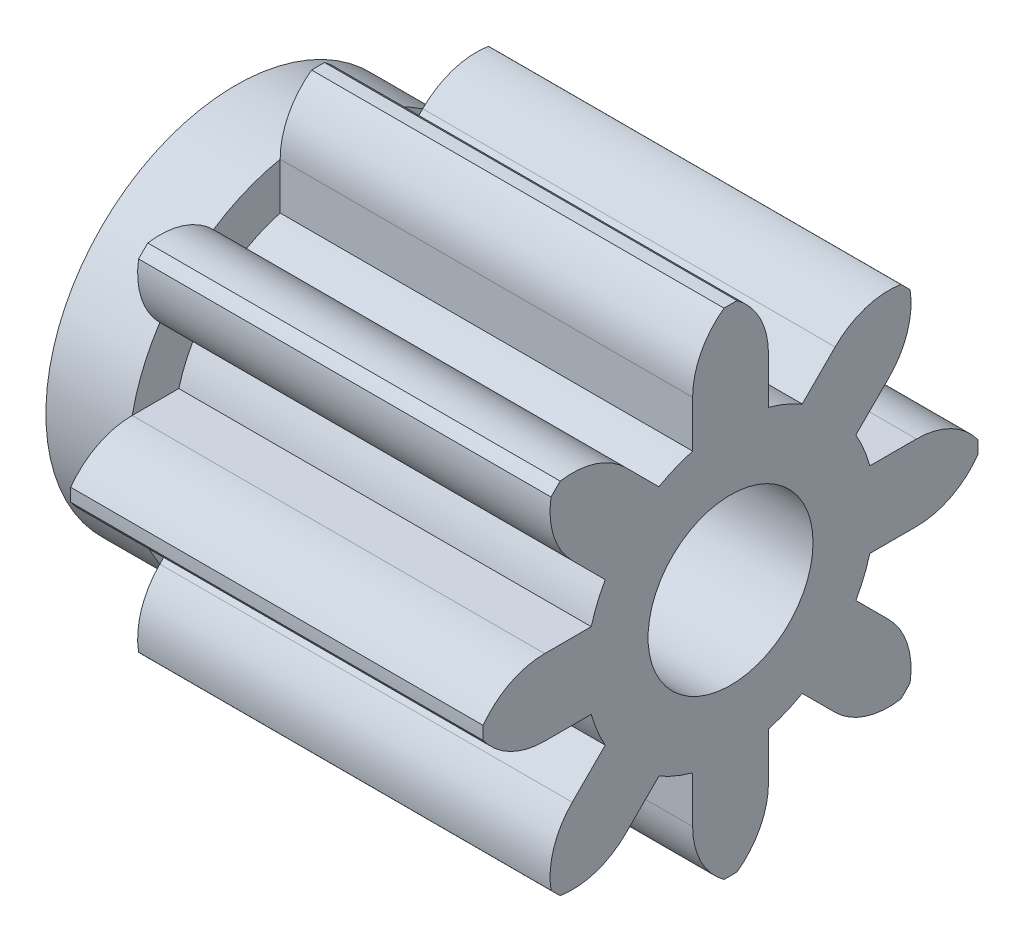
SolidWorks part; units mm, degrees
ref_plane "Front Plane" through (0, 0, 0) normal (0, 0, 1) x (1, 0, 0)
ref_plane "Top Plane" through (0, 0, 0) normal (0, 1, 0) x (1, 0, 0)
ref_plane "Right Plane" through (0, 0, 0) normal (1, 0, 0) x (0, 0, -1)
sketch "Sketch1" plane through (0, 0, 0) normal (1, 0, 0) x (0, 0, -1)
  circle A0 centre (0, 0) radius 2.3
  dimension "D1" = 4.6
extrude "Boss-Extrude1" add sketch "Sketch1" along normal blind 1
sketch "Sketch2" plane through (1, 0, 0) normal (1, 0, 0) x (0, 0, -1)
  circle A0 centre (0, 0) radius 1.75
  circle A1 centre (0, 0) radius 1
  dimension "D1" = 3.5
  dimension "D2" = 2
extrude "Boss-Extrude2" add sketch "Sketch2" along normal blind 5
sketch "Sketch3" plane through (1, 0, 0) normal (1, 0, 0) x (0, 0, -1)
  line L0 (-0.4598, 2.2536) -> (-0.4598, 1.6885)
  line L1 (0.4598, 2.2536) -> (0.4598, 1.6885)
  circle A0 centre (0, 0) radius 1.75 construction
  circle A1 centre (0, 0) radius 1.75
  circle A2 centre (0, 0) radius 2.3 construction
  circle A3 centre (0, 0) radius 2.3
  circle A4 centre (0, 0) radius 3
  circle A5 centre (0.4598, 2.2536) radius 0.9196
  circle A6 centre (1.3059, 1.8933) radius 0.9196
  circle A7 centre (1.9433, 1.2303) radius 0.9196
  circle A8 centre (-0.4598, 2.2536) radius 0.9196
  point P17 (0, 3.05)
  circle M2 centre (0, 0) radius 1.75
  circle M3 centre (0, 0) radius 2.3
  dimension "D1" = 6
  dimension "D2" = 3.05
extrude "Boss-Extrude3" add sketch "Sketch3" along normal up to surface (5 mm away) separate body contours A8 A6 M2 | A8 A6 L1 M2 | A6 A8 | A1 A8 A6 A5 M3 | A5 L0 M2 | A8 A4 A5 M3
pattern_circular "CirPattern1" count 8 over 360 about axis through (0, 0, 0) along (1, 0, 0) of bodies 103
combine bodies "Combine1" bodies to combine 103 110 109 107 106 102 104 105 108
